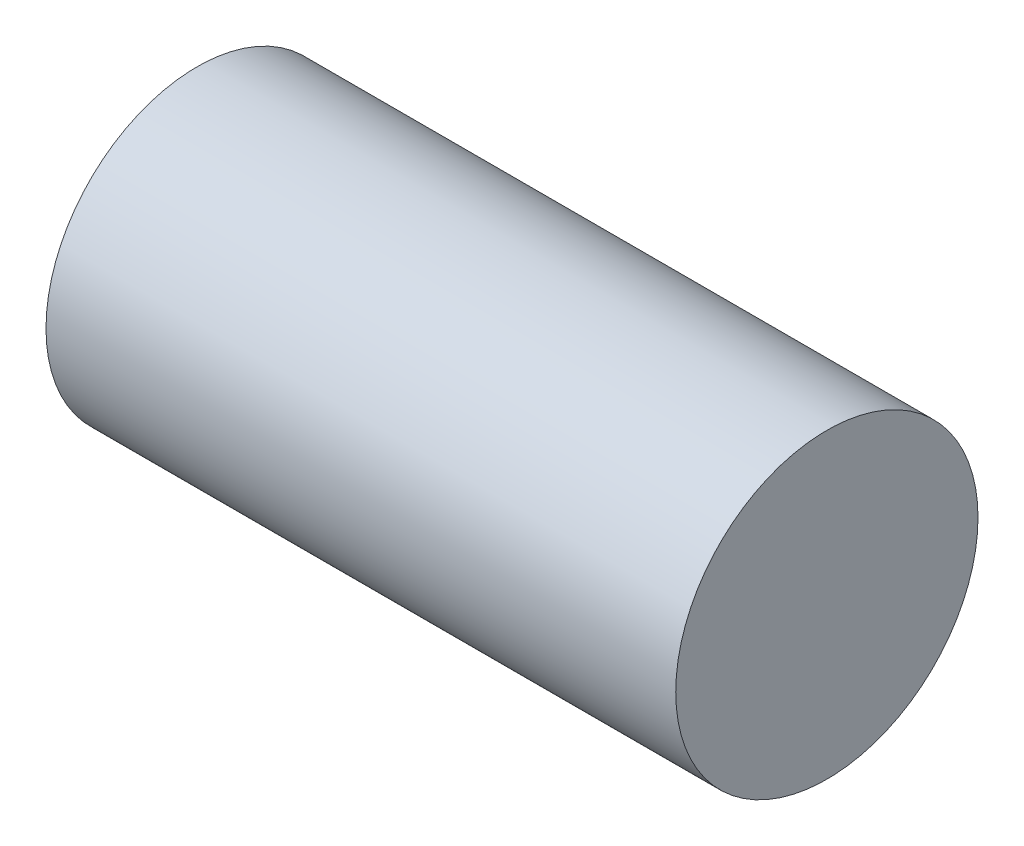
SolidWorks part; units mm, degrees
ref_plane "Front Plane" through (0, 0, 0) normal (0, 0, 1) x (1, 0, 0)
ref_plane "Top Plane" through (0, 0, 0) normal (0, 1, 0) x (1, 0, 0)
ref_plane "Right Plane" through (0, 0, 0) normal (1, 0, 0) x (0, 0, -1)
sketch "Sketch1" plane through (0, 0, 0) normal (0, 0, 1) x (1, 0, 0)
  line L0 (0, 0) -> (10, 0)
  dimension "D1" = 10
revolve "Revolve-Thin1" add sketch "Sketch1" angle 360 about L0 wall 2.4
